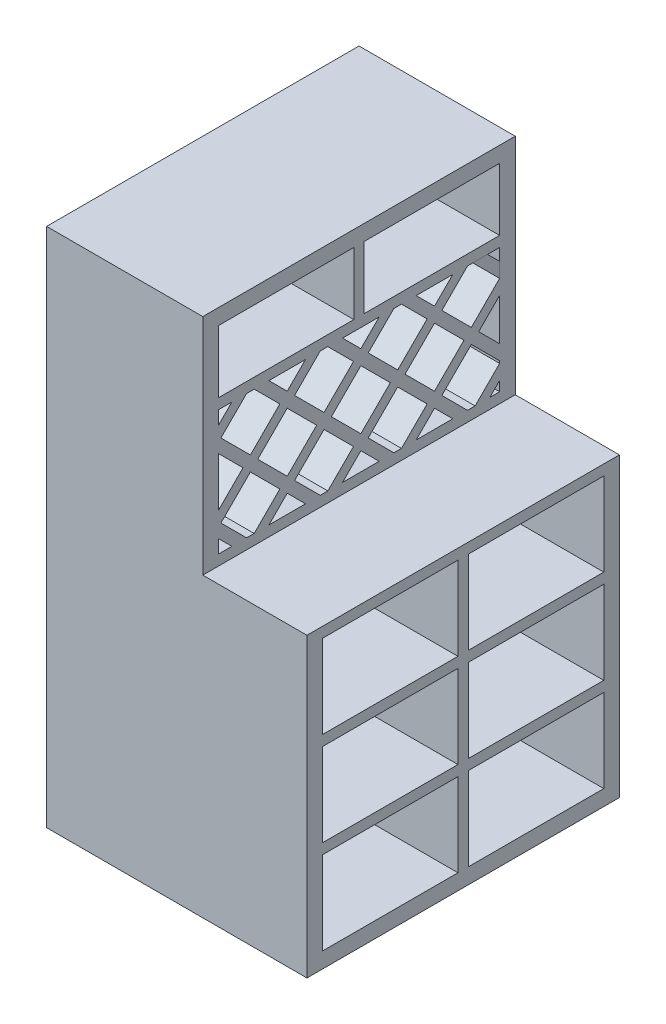
SolidWorks part; units mm, degrees
material "Zinc AC41A Alloy, As Cast"
ref_plane "Front Plane" through (0, 0, 0) normal (0, 0, 1) x (1, 0, 0)
ref_plane "Top Plane" through (0, 0, 0) normal (0, 1, 0) x (1, 0, 0)
ref_plane "Right Plane" through (0, 0, 0) normal (1, 0, 0) x (0, 0, -1)
sketch "Sketch1" plane through (0, 0, 0) normal (0, 0, 1) x (1, 0, 0)
  line L0 (-25, 58.4239) -> (-25, -41.5761)
  line L1 (-25, -41.5761) -> (25, -41.5761)
  line L2 (25, -41.5761) -> (25, 15.4239)
  line L3 (25, 15.4239) -> (5, 15.4239)
  line L4 (5, 15.4239) -> (5, 58.4239)
  line L5 (5, 58.4239) -> (-25, 58.4239)
  point P2 (0, -41.5761)
  dimension "D1" = 100
  dimension "D2" = 50
  dimension "D3" = 57
  dimension "D4" = 30
extrude "Boss-Extrude1" add sketch "Sketch1" along normal mid plane 60
sketch "Sketch2" plane through (25, 0, 0) normal (1, 0, 0) x (0, 0, -1)
  line L0 (-30, -41.5761) -> (-30, 15.4239) construction
  line L1 (-27, 13.4239) -> (-1, 13.4239)
  line L2 (-27, 13.4239) -> (-27, -2.5761)
  line L3 (-27, -2.5761) -> (-1, -2.5761)
  line L4 (-1, 13.4239) -> (-1, -2.5761)
  line L5 (-27, 13.4239) -> (-1, -2.5761) construction
  line L6 (-27, -2.5761) -> (-1, 13.4239) construction
  line L7 (-30, 15.4239) -> (30, 15.4239) construction
  line L8 (1, 13.4239) -> (1, -2.5761)
  line L9 (1, 13.4239) -> (27, 13.4239)
  line L10 (27, 13.4239) -> (27, -2.5761)
  line L11 (1, -2.5761) -> (27, -2.5761)
  line L12 (0, 15.4239) -> (0, -41.5761) construction
  line L13 (-30, 15.4239) -> (30, 15.4239) construction
  line L14 (-30, -41.5761) -> (30, -41.5761) construction
  line L15 (-30, -13.0761) -> (30, -13.0761) construction
  line L16 (30, -41.5761) -> (30, 15.4239) construction
  line L17 (-27, -4.5761) -> (-1, -4.5761)
  line L18 (-1, -4.5761) -> (-1, -20.5761)
  line L19 (-27, -4.5761) -> (-27, -20.5761)
  line L20 (-27, -20.5761) -> (-1, -20.5761)
  line L21 (27, -4.5761) -> (27, -20.5761)
  line L22 (1, -20.5761) -> (27, -20.5761)
  line L23 (1, -4.5761) -> (27, -4.5761)
  line L24 (1, -4.5761) -> (1, -20.5761)
  line L25 (1, -22.5761) -> (27, -22.5761)
  line L26 (1, -22.5761) -> (1, -38.5761)
  line L27 (27, -22.5761) -> (27, -38.5761)
  line L28 (1, -38.5761) -> (27, -38.5761)
  line L29 (-27, -22.5761) -> (-1, -22.5761)
  line L30 (-27, -22.5761) -> (-27, -38.5761)
  line L31 (-1, -22.5761) -> (-1, -38.5761)
  line L32 (-27, -38.5761) -> (-1, -38.5761)
  point P0 (-14, 5.4239)
  dimension "D1" = 16
  dimension "D2" = 26
  dimension "D3" = 3
  dimension "D4" = 2
  dimension "D6" = 3
  dimension "D7" = 2
  dimension "D8" = 16
  dimension "D9" = 16
  dimension "D10" = 26
  dimension "D11" = 3
  dimension "D12" = 2
  dimension "D13" = 3
  dimension "D14" = 2
  dimension "D15" = 3
  dimension "D16" = 3
  dimension "D17" = 2
  dimension "D18" = 2
  dimension "D19" = 3
  dimension "D20" = 3
  dimension "D21" = 26
  dimension "D22" = 26
  dimension "D23" = 2
  dimension "D5" = 2
extrude "Cut-Extrude1" cut sketch "Sketch2" against normal through all
sketch "Sketch3" plane through (5, 0, 0) normal (1, 0, 0) x (0, 0, -1)
  line L0 (0, 58.4239) -> (0, 15.4239) construction
  line L1 (-30, 58.4239) -> (30, 58.4239) construction
  line L2 (-30, 15.4239) -> (30, 15.4239) construction
  line L3 (30, 15.4239) -> (30, 58.4239) construction
  line L4 (1, 55.4239) -> (27, 55.4239)
  line L5 (1, 55.4239) -> (1, 43.4239)
  line L6 (1, 43.4239) -> (27, 43.4239)
  line L7 (27, 55.4239) -> (27, 43.4239)
  line L8 (1, 55.4239) -> (27, 43.4239) construction
  line L9 (1, 43.4239) -> (27, 55.4239) construction
  point P6 (14, 49.4239)
  dimension "D1" = 26
  dimension "D2" = 12
  dimension "D3" = 3
  dimension "D4" = 3
extrude "Cut-Extrude2" cut sketch "Sketch3" against normal through all
mirror "Mirror2" about plane through (0, 0, 0) normal (0, 0, 1) of "Cut-Extrude2"
sketch "Sketch4" plane through (5, 0, 0) normal (1, 0, 0) x (0, 0, -1)
  line L0 (30, 15.4239) -> (30, 58.4239) construction
  line L1 (-27, 41.4239) -> (-24.4204, 41.4239)
  line L2 (-27, 41.4239) -> (-27, 38.8444)
  line L3 (-27, 17.4239) -> (-24.4204, 17.4239)
  line L4 (27, 41.4239) -> (27, 36.2758)
  line L5 (-19.9289, 29.903) -> (-14.521, 24.495) construction
  line L6 (-27, 17.4239) -> (-25.2142, 18.2176) construction
  line L7 (-30, 15.4239) -> (-30, 58.4239) construction
  line L8 (1, 43.4239) -> (27, 43.4239) construction
  line L9 (-30, 15.4239) -> (30, 15.4239) construction
  line L10 (-26.521, 22.3528) -> (-21.592, 17.4239)
  line L11 (-20.1362, 41.4239) -> (-15.2072, 36.495)
  line L12 (-17.3077, 41.4239) -> (-13.793, 37.9092)
  line L13 (-27, 20.0035) -> (-24.4204, 17.4239)
  line L14 (-26.521, 36.495) -> (-20.8641, 30.8381)
  line L15 (-27, 34.1456) -> (-22.2783, 29.4239)
  line L16 (-21.3431, 28.4887) -> (-15.9352, 23.0808) construction
  line L17 (-19.9289, 44.0451) -> (-0.3788, 24.495) construction
  line L18 (-19.9289, 41.2167) -> (-3.2072, 24.495) construction
  line L19 (-28.4142, 21.4177) -> (-23.0062, 16.0097) construction
  line L20 (-5.994, 41.4239) -> (-1.0651, 36.495)
  line L21 (-3.1656, 41.4239) -> (0.3491, 37.9092)
  line L22 (-13.0651, 48.495) -> (10.9349, 24.495) construction
  line L23 (-10.2367, 48.495) -> (13.7633, 24.495) construction
  line L24 (8.1481, 41.4239) -> (13.077, 36.495)
  line L25 (10.9765, 41.4239) -> (14.4912, 37.9092)
  line L26 (1.077, 48.495) -> (25.077, 24.495) construction
  line L27 (3.9055, 48.495) -> (27.9055, 24.495) construction
  line L28 (-27, 29.4239) -> (-22.2783, 29.4239) construction
  line L29 (-26.521, 36.495) -> (-21.592, 41.4239)
  line L30 (-27, 38.8444) -> (-24.4204, 41.4239)
  line L31 (-28.4142, 37.4301) -> (-23.0062, 42.8381) construction
  line L32 (-27, 24.7022) -> (-22.2783, 29.4239)
  line L33 (-19.9289, 31.7733) -> (-17.3494, 34.3528) construction
  line L34 (-26.521, 22.3528) -> (-20.8641, 28.0097)
  line L35 (-19.9289, 28.9449) -> (-14.521, 34.3528) construction
  line L36 (-20.1362, 17.4239) -> (-15.2072, 22.3528)
  line L37 (-19.9289, 17.6312) -> (-3.2072, 34.3528) construction
  line L38 (-5.994, 17.4239) -> (-1.0651, 22.3528)
  line L39 (-17.3077, 17.4239) -> (-13.793, 20.9386)
  line L40 (-18.722, 16.0097) -> (5.278, 40.0097) construction
  line L41 (-13.0651, 10.3528) -> (10.9349, 34.3528) construction
  line L42 (-3.1656, 17.4239) -> (0.3491, 20.9386)
  line L43 (8.1481, 17.4239) -> (13.077, 22.3528)
  line L44 (10.9765, 17.4239) -> (14.4912, 20.9386)
  line L45 (25.1187, 17.4239) -> (27, 19.3053)
  line L46 (22.2902, 17.4239) -> (27, 22.1337)
  line L47 (-11.6509, 8.9386) -> (19.4202, 40.0097) construction
  line L48 (-5.994, 3.2818) -> (25.077, 34.3528) construction
  line L49 (-4.5798, 1.8676) -> (26.4912, 32.9386) construction
  line L50 (2.4912, -5.2035) -> (33.5623, 25.8676) construction
  line L51 (-13.0651, 10.3528) -> (18.006, 41.4239) construction
  line L52 (1.077, -3.7893) -> (32.1481, 27.2818) construction
  line L53 (-21.592, 41.4239) -> (-20.1362, 41.4239)
  line L54 (-27, 36.974) -> (-7.4499, 17.4239) construction
  line L55 (-27, 34.1456) -> (-27, 24.7022)
  line L56 (-27, 36.0159) -> (-21.592, 41.4239) construction
  line L57 (-17.3077, 41.4239) -> (-10.2783, 41.4239)
  line L58 (-13.793, 37.9092) -> (-10.2783, 41.4239)
  line L59 (-27, 24.7022) -> (-10.2783, 41.4239) construction
  line L60 (-12.3788, 36.495) -> (-7.4499, 41.4239)
  line L61 (-12.3788, 36.495) -> (-6.722, 30.8381)
  line L62 (-17.3077, 41.4239) -> (6.6923, 17.4239) construction
  line L63 (-7.4499, 41.4239) -> (-5.994, 41.4239)
  line L64 (-13.793, 35.0808) -> (-8.1362, 29.4239)
  line L65 (-20.1362, 41.4239) -> (3.8638, 17.4239) construction
  line L66 (-19.4499, 29.4239) -> (-13.793, 23.7671)
  line L67 (-19.4499, 29.4239) -> (-8.1362, 29.4239) construction
  line L68 (-27, 20.0035) -> (-27, 17.4239)
  line L69 (-27, 22.8319) -> (-21.592, 17.4239) construction
  line L70 (-20.8641, 28.0097) -> (-15.2072, 22.3528)
  line L71 (-27, 34.1456) -> (-10.2783, 17.4239) construction
  line L72 (-20.8641, 30.8381) -> (-15.2072, 36.495)
  line L73 (-17.3077, 17.4239) -> (-10.2783, 17.4239)
  line L74 (-13.793, 20.9386) -> (-10.2783, 17.4239)
  line L75 (-12.3788, 22.3528) -> (-7.4499, 17.4239)
  line L76 (-6.722, 28.0097) -> (-1.0651, 22.3528)
  line L77 (-5.3077, 29.4239) -> (6.006, 29.4239) construction
  line L78 (-5.3077, 29.4239) -> (0.3491, 23.7671)
  line L79 (0.3491, 35.0808) -> (6.006, 29.4239)
  line L80 (-5.994, 41.4239) -> (18.006, 17.4239) construction
  line L81 (1.7633, 36.495) -> (7.4202, 30.8381)
  line L82 (-3.1656, 41.4239) -> (20.8344, 17.4239) construction
  line L83 (6.6923, 41.4239) -> (8.1481, 41.4239)
  line L84 (-3.1656, 41.4239) -> (3.8638, 41.4239)
  line L85 (10.9765, 41.4239) -> (18.006, 41.4239)
  line L86 (14.4912, 37.9092) -> (18.006, 41.4239)
  line L87 (15.9055, 36.495) -> (20.8344, 41.4239)
  line L88 (15.9055, 36.495) -> (21.5623, 30.8381)
  line L89 (20.8344, 41.4239) -> (27, 41.4239)
  line L90 (21.5623, 30.8381) -> (27, 36.2758)
  line L91 (22.9765, 29.4239) -> (27, 29.4239) construction
  line L92 (22.9765, 29.4239) -> (27, 33.4474)
  line L93 (27, 22.572) -> (27, 22.1337)
  line L94 (27, 33.4474) -> (27, 25.4004)
  line L95 (22.9765, 29.4239) -> (27, 25.4004)
  line L96 (27, 19.3053) -> (27, 17.4239)
  line L97 (25.1187, 17.4239) -> (27, 17.4239)
  line L98 (0.3491, 23.7671) -> (6.006, 29.4239)
  line L99 (1.7633, 22.3528) -> (7.4202, 28.0097)
  line L100 (6.6923, 17.4239) -> (8.1481, 17.4239)
  line L101 (10.9765, 17.4239) -> (18.006, 17.4239)
  line L102 (14.4912, 20.9386) -> (18.006, 17.4239)
  line L103 (15.9055, 22.3528) -> (20.8344, 17.4239)
  line L104 (21.5623, 28.0097) -> (27, 22.572)
  line L105 (15.9055, 22.3528) -> (21.5623, 28.0097)
  line L106 (20.8344, 17.4239) -> (22.2902, 17.4239)
  line L107 (14.4912, 35.0808) -> (20.1481, 29.4239)
  line L108 (8.8344, 29.4239) -> (14.4912, 23.7671)
  line L109 (8.8344, 29.4239) -> (20.1481, 29.4239) construction
  line L110 (7.4202, 28.0097) -> (13.077, 22.3528)
  line L111 (1.7633, 22.3528) -> (6.6923, 17.4239)
  line L112 (0.3491, 20.9386) -> (3.8638, 17.4239)
  line L113 (-3.1656, 17.4239) -> (3.8638, 17.4239)
  line L114 (1.7633, 36.495) -> (6.6923, 41.4239)
  line L115 (7.4202, 30.8381) -> (13.077, 36.495)
  line L116 (8.8344, 29.4239) -> (14.4912, 35.0808)
  line L117 (14.4912, 23.7671) -> (20.1481, 29.4239)
  line L118 (-21.592, 17.4239) -> (-20.1362, 17.4239)
  line L119 (-6.722, 30.8381) -> (-1.0651, 36.495)
  line L120 (-20.1362, 17.4239) -> (3.8638, 41.4239) construction
  line L121 (-5.3077, 29.4239) -> (0.3491, 35.0808)
  line L122 (-19.4499, 29.4239) -> (-13.793, 35.0808)
  line L123 (-13.793, 23.7671) -> (-8.1362, 29.4239)
  line L124 (-12.3788, 22.3528) -> (-6.722, 28.0097)
  line L125 (-7.4499, 17.4239) -> (-5.994, 17.4239)
  line L126 (0.3491, 37.9092) -> (3.8638, 41.4239)
  point P0 (0, 29.4239)
  point P11 (14, 43.4239)
  dimension "D1" = 3
  dimension "D2" = 3
  dimension "D3" = 2
  dimension "D4" = 2
  dimension "D5" = 45
  dimension "D15" = 2.5796
  dimension "D6" = 2
  dimension "D17" = 10
  dimension "D19" = 10
  dimension "D21" = 2
  dimension "D22" = 2
extrude "Cut-Extrude3" cut sketch "Sketch4" against normal through all
sketch "Sketch5" plane through (5, 0, 0) normal (1, 0, 0) x (0, 0, -1)
  line L0 (27, 36.2758) -> (21.8519, 41.4239)
  line L1 (27, 41.4239) -> (20.8344, 41.4239) construction
  line L2 (21.8519, 41.4239) -> (24.6803, 41.4239)
  line L3 (24.6803, 41.4239) -> (27, 39.1042)
  line L4 (27, 36.2758) -> (27, 41.4239) construction
  line L5 (27, 39.1042) -> (27, 36.2758)
  line L6 (15.9055, 36.495) -> (21.5623, 30.8381) construction
  dimension "D1" = 2
extrude "Boss-Extrude2" add sketch "Sketch5" along direction (1, 0, 0) on the side against the normal through all separate body
